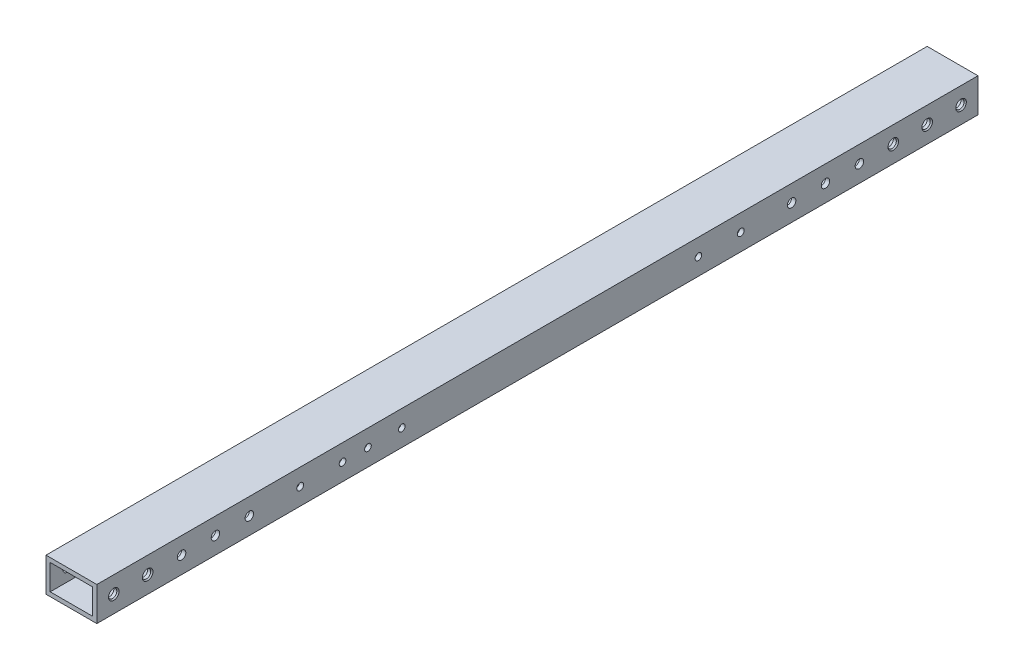
SolidWorks part; units mm, degrees
ref_plane "Front Plane" through (0, 0, 0) normal (0, 0, 1) x (1, 0, 0)
ref_plane "Top Plane" through (0, 0, 0) normal (0, 1, 0) x (1, 0, 0)
ref_plane "Right Plane" through (0, 0, 0) normal (1, 0, 0) x (0, 0, -1)
sketch "Sketch1" plane through (0, 0, 0) normal (0, 0, 1) x (1, 0, 0)
  line L0 (-15.875, 9.525) -> (15.875, 9.525)
  line L2 (-19.05, 12.7) -> (19.05, 12.7)
  line L3 (-19.05, 12.7) -> (-19.05, -12.7)
  line L4 (-19.05, -12.7) -> (19.05, -12.7)
  line L5 (19.05, 12.7) -> (19.05, -12.7)
  line L10 (15.875, 9.525) -> (15.875, -9.525)
  line L11 (-15.875, -9.525) -> (15.875, -9.525)
  line L12 (-15.875, 9.525) -> (-15.875, -9.525)
  point P12 (0, 12.7)
  point P14 (19.05, 0)
  dimension "Wall Thickness" = 3.175
  dimension "Outside Width" = 38.1
  dimension "Outside Height" = 25.4
  dimension "Inside Height" = 19.05
  dimension "Inside Width" = 31.75
sketch "Sketch2" plane through (0, 0, 0) normal (1, 0, 0) x (0, 0, -1)
  line L0 (330.2, 0) -> (-330.2, 0)
  point P4 (0, 0)
  point P7 (-330.2, 0)
  point P10 (330.2, 0)
  dimension "Length" = 660.4
sketch "Sketch3" plane through (0, 0, 0) normal (0, 0, 1) x (1, 0, 0)
  line L21 (19.05, 12.7) -> (-19.05, 12.7)
  line L22 (19.05, -12.7) -> (19.05, 12.7)
  line L23 (-19.05, -12.7) -> (19.05, -12.7)
  line L24 (-19.05, 12.7) -> (-19.05, -12.7)
  line L25 (19.05, 12.7) -> (-19.05, 12.7)
  line L26 (19.05, -12.7) -> (19.05, 12.7)
  line L27 (-19.05, -12.7) -> (19.05, -12.7)
  line L28 (-19.05, 12.7) -> (-19.05, -12.7)
  line L29 (15.875, 9.525) -> (-15.875, 9.525)
  line L30 (15.875, -9.525) -> (15.875, 9.525)
  line L31 (-15.875, -9.525) -> (15.875, -9.525)
  line L32 (-15.875, 9.525) -> (-15.875, -9.525)
  line L33 (15.875, 9.525) -> (-15.875, 9.525)
  line L34 (15.875, -9.525) -> (15.875, 9.525)
  line L35 (-15.875, -9.525) -> (15.875, -9.525)
  line L36 (-15.875, 9.525) -> (-15.875, -9.525)
  dimension "D1" = 0
  dimension "D2" = 0
extrude "Boss-Extrude1" add sketch "Sketch3" along normal up to vertex (330.2 mm away) and the other way up to vertex (330.2 mm away) up to point (0, 0, 330.2) other way up to point (0, 0, -330.2)
sketch "Drawing Reference" plane through (0, 0, 0) normal (1, 0, 0) x (0, 0, -1)
  line L0 (-330.2, 0) -> (330.2, 0) construction
  line L1 (0, -12.7) -> (0, 12.7) construction
  line L2 (-330.2, -12.7) -> (330.2, -12.7) construction
  line L5 (-330.2, 12.7) -> (330.2, 12.7) construction
  point P7 (-302.768, 0)
  point P8 (302.768, 0)
  dimension "D1" = 27.432
sketch "Sketch4" plane through (-19.05, 0, 0) normal (-1, 0, 0) x (0, 0, 1)
  line L0 (-330.2, 0) -> (-317.5, 0)
  line L1 (-330.2, 12.7) -> (-330.2, -12.7) construction
  line L2 (-317.5, 0) -> (-292.1, 0)
  line L3 (-292.1, 0) -> (-266.7, 0)
  line L4 (-266.7, 0) -> (-241.3, 0)
  line L5 (-241.3, 0) -> (-215.9, 0)
  line L6 (-215.9, 0) -> (-190.5, 0)
  line L7 (330.2, 0) -> (317.5, 0)
  line L8 (330.2, 12.7) -> (330.2, -12.7) construction
  line L9 (317.5, 0) -> (292.1, 0)
  line L10 (292.1, 0) -> (266.7, 0)
  line L11 (266.7, 0) -> (241.3, 0)
  line L12 (241.3, 0) -> (215.9, 0)
  line L13 (-190.5, 0) -> (-120.65, 0)
  line L14 (-190.5, 0) -> (-152.4, 0) construction
  line L15 (215.9, 0) -> (146.05, 0)
hole_wizard "1/4 (0.25) Diameter Hole2" positions "Sketch7" profile "Sketch8" hole size "1/4" standard "ANSI Inch" end condition through all
sketch "Sketch7" plane through (-19.05, 0, 0) normal (-1, 0, 0) x (0, 0, 1)
  point P0 (-317.5, 0)
  point P3 (-292.1, 0)
  point P7 (317.5, 0)
  point P11 (-266.7, 0)
  point P14 (292.1, 0)
sketch "Sketch8" plane through (-19.05, 0, -317.5) normal (0, 1, 0) x (0, 0, 1)
  line L0 (0, 0) -> (0, 38.1)
  line L1 (0, 38.1) -> (3.9624, 38.1)
  line L2 (3.175, 37.1942) -> (3.175, 0)
  line L5 (3.175, 0) -> (0, 0)
  line L7 (3.9624, 38.1) -> (3.175, 37.1942)
  line L8 (-3.9624, 38.1) -> (-3.175, 37.1942) construction
  line L11 (0, -6.35) -> (0, 107.95) construction
  dimension "Thru Hole Dia." = 6.35
  dimension "Thru Hole Depth" = 38.1
  dimension "Far C'Sink Dia." = 7.9248
  dimension "Far C'Sink Angle" = 82
hole_wizard "1/4 (0.25) Diameter Hole3" positions "Sketch9" profile "Sketch10" hole size "1/4" standard "ANSI Inch" end condition through all
sketch "Sketch9" plane through (19.05, 0, 0) normal (1, 0, 0) x (0, 0, -1)
  point P0 (-266.7, 0)
  point P3 (-241.3, 0)
  point P6 (-215.9, 0)
  point P9 (241.3, 0)
  point P12 (215.9, 0)
  point P15 (190.5, 0)
sketch "Sketch10" plane through (19.05, 0, 266.7) normal (0, 1, 0) x (0, 0, -1)
  line L0 (0, 0) -> (0, 38.1)
  line L1 (0, 38.1) -> (3.175, 38.1)
  line L2 (3.175, 38.1) -> (3.175, 0)
  line L5 (3.175, 0) -> (0, 0)
  line L11 (0, -6.35) -> (0, 107.95) construction
  dimension "Thru Hole Dia." = 6.35
  dimension "Thru Hole Depth" = 38.1
hole_wizard "13/64 (0.20313) Diameter Hole1" positions "Sketch11" profile "Sketch12" hole size "13/64" standard "ANSI Inch" end condition through all
sketch "Sketch11" plane through (19.05, 0, 0) normal (1, 0, 0) x (0, 0, -1)
  point P0 (152.4, 0)
  point P7 (-177.8, 0)
sketch "Sketch12" plane through (19.05, 0, -152.4) normal (0, 1, 0) x (0, 0, -1)
  line L0 (0, 0) -> (0, 38.1)
  line L1 (0, 38.1) -> (2.5798, 38.1)
  line L2 (2.5798, 38.1) -> (2.5798, 0)
  line L5 (2.5798, 0) -> (0, 0)
  line L11 (0, -6.35) -> (0, 107.95) construction
  dimension "Thru Hole Dia." = 5.1595
  dimension "Thru Hole Depth" = 38.1
hole_wizard "#10 Clearance Hole1" positions "Sketch13" profile "Sketch14" hole size "#10" standard "ANSI Inch" end condition through all
sketch "Sketch13" plane through (-19.05, 0, 0) normal (-1, 0, 0) x (0, 0, 1)
  point P0 (-120.65, 0)
  point P3 (146.05, 0)
  point P10 (127, 0)
  point P13 (101.6, 0)
sketch "Sketch14" plane through (-19.05, 0, -120.65) normal (0, 1, 0) x (0, 0, 1)
  line L0 (0, 0) -> (0, 38.1)
  line L1 (0, 38.1) -> (2.4892, 38.1)
  line L2 (2.4892, 38.1) -> (2.4892, 0)
  line L5 (2.4892, 0) -> (0, 0)
  line L11 (0, -6.35) -> (0, 107.95) construction
  dimension "Thru Hole Dia." = 4.9784
  dimension "Thru Hole Depth" = 38.1
equation "\"D1@Drawing Reference\"=\"Outside Width@Sketch1\" * 0.72"
